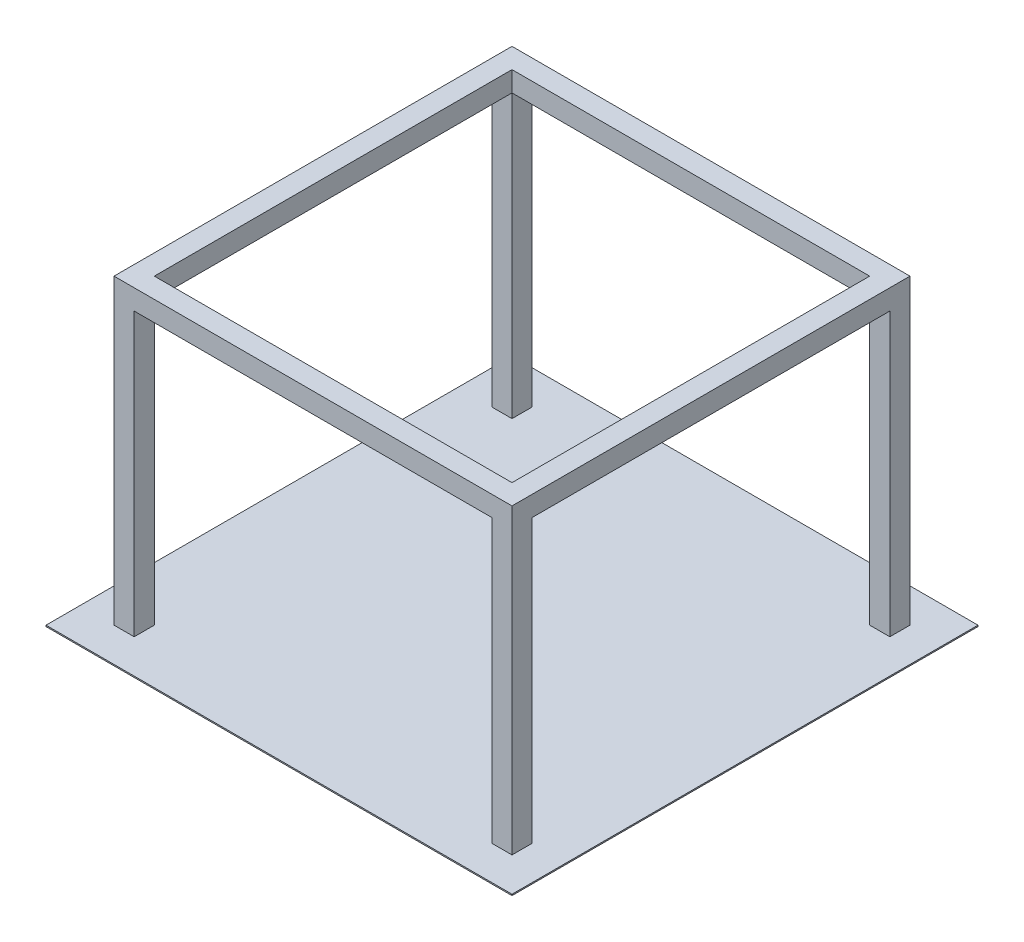
SolidWorks part; units mm, degrees
ref_plane "Front Plane" through (0, 0, 0) normal (0, 0, 1) x (1, 0, 0)
ref_plane "Top Plane" through (0, 0, 0) normal (0, 1, 0) x (1, 0, 0)
ref_plane "Right Plane" through (0, 0, 0) normal (1, 0, 0) x (0, 0, -1)
sketch "Sketch1" plane through (0, 0, 0) normal (0, 1, 0) x (1, 0, 0)
  line L1 (-925, 925) -> (925, 925)
  line L2 (-925, 925) -> (-925, -925)
  line L3 (-925, -925) -> (925, -925)
  line L4 (925, 925) -> (925, -925)
  line L5 (-925, 925) -> (925, -925) construction
  line L6 (-925, -925) -> (925, 925) construction
  point P0 (0, 0)
  dimension "D1" = 1850
extrude "Boss-Extrude1" add sketch "Sketch1" along normal blind 5
sketch "Sketch2" plane through (0, 5, 0) normal (0, 1, 0) x (1, 0, 0)
  line L1 (-790, -790) -> (790, -790)
  line L2 (-790, -790) -> (-790, 790)
  line L3 (-790, 790) -> (790, 790)
  line L4 (790, -790) -> (790, 790)
  line L5 (-790, -790) -> (790, 790) construction
  line L6 (-790, 790) -> (790, -790) construction
  point P0 (0, 0)
  dimension "D1" = 1580
extrude "Boss-Extrude2" add sketch "Sketch2" along normal blind 1200 separate body
sketch "Sketch3" plane through (0, 0, 0) normal (0, 0, 1) x (1, 0, 0)
  line L0 (-925, 5) -> (925, 5) construction
  line L1 (-710, 5) -> (710, 5)
  line L2 (-710, 5) -> (-710, 1125)
  line L3 (-710, 1125) -> (710, 1125)
  line L4 (710, 5) -> (710, 1125)
  line L5 (-710, 5) -> (710, 1125) construction
  line L6 (-710, 1125) -> (710, 5) construction
  line L7 (790, 1205) -> (790, 5) construction
  line L8 (-790, 1205) -> (790, 1205) construction
  point P4 (0, 565)
  dimension "D1" = 80
  dimension "D2" = 80
extrude "Cut-Extrude1" cut sketch "Sketch3" against normal through all both and the other way through all
sketch "Sketch4" plane through (0, 0, 0) normal (1, 0, 0) x (0, 0, -1)
  line L0 (-790, 5) -> (790, 5) construction
  line L1 (-710, 5) -> (710, 5)
  line L2 (-710, 5) -> (-710, 1125)
  line L3 (-710, 1125) -> (710, 1125)
  line L4 (710, 5) -> (710, 1125)
  line L5 (-710, 5) -> (710, 1125) construction
  line L6 (-710, 1125) -> (710, 5) construction
  line L7 (790, 1205) -> (790, 5) construction
  line L8 (-790, 1205) -> (790, 1205) construction
  point P4 (0, 565)
  point P5 (0, 0)
  dimension "D1" = 80
  dimension "D2" = 80
extrude "Cut-Extrude2" cut sketch "Sketch4" against normal through all both and the other way through all
sketch "Sketch5" plane through (0, 1205, 0) normal (0, 1, 0) x (1, 0, 0)
  line L0 (790, -790) -> (790, 790) construction
  line L1 (-710, 710) -> (710, 710)
  line L2 (-710, 710) -> (-710, -710)
  line L3 (-710, -710) -> (710, -710)
  line L4 (710, 710) -> (710, -710)
  line L5 (-710, 710) -> (710, -710) construction
  line L6 (-710, -710) -> (710, 710) construction
  line L7 (790, 790) -> (-790, 790) construction
  point P0 (0, 0)
  dimension "D1" = 80
  dimension "D2" = 80
extrude "Cut-Extrude3" cut sketch "Sketch5" against normal up to next (80 mm away)
ref_point "Global Frame Origin"
